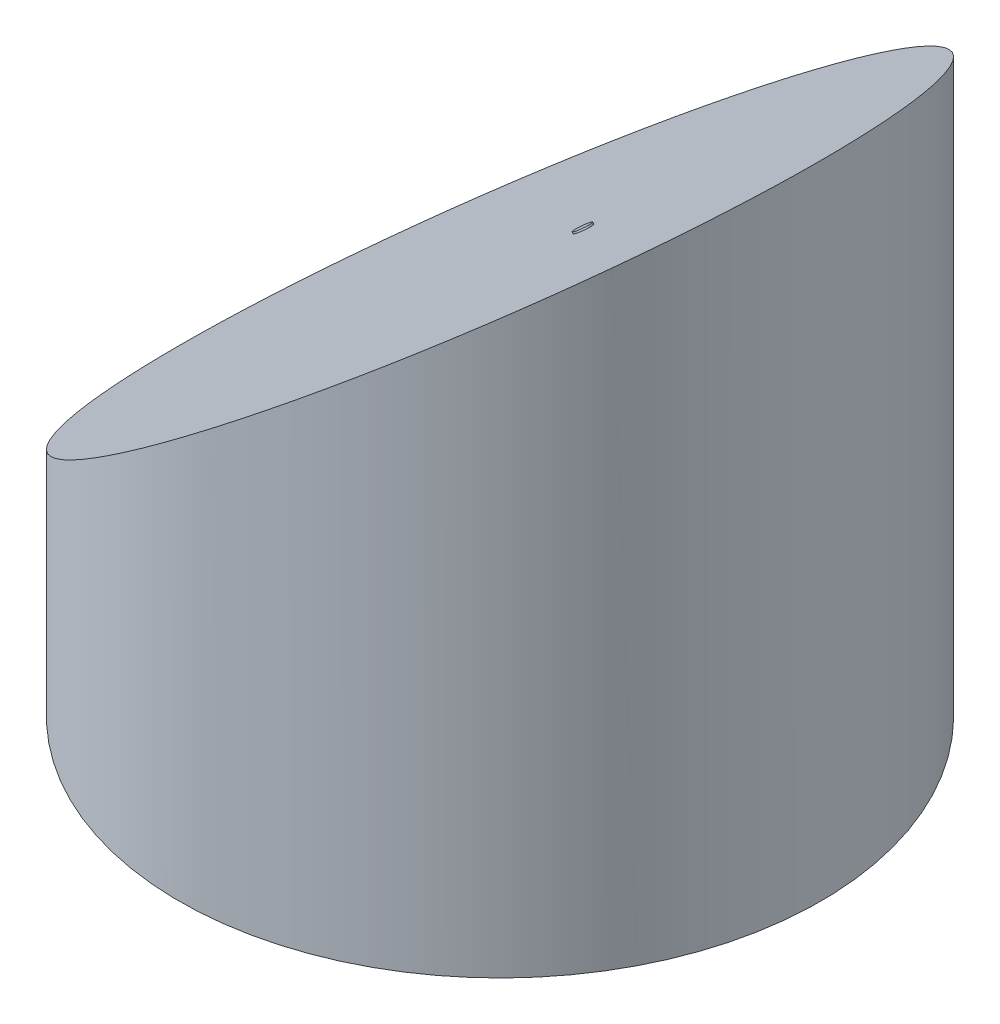
SolidWorks part; units mm, degrees
ref_plane "Front Plane" through (0, 0, 0) normal (0, 0, 1) x (1, 0, 0)
ref_plane "Top Plane" through (0, 0, 0) normal (0, 1, 0) x (1, 0, 0)
ref_plane "Right Plane" through (0, 0, 0) normal (1, 0, 0) x (0, 0, -1)
sketch "Sketch1" plane through (0, 0, 0) normal (0, 0, 1) x (1, 0, 0)
  line L0 (0, 3000) -> (0, -1000)
  line L1 (0, -1000) -> (-2000, -1000)
  line L2 (-2000, -1000) -> (-2000, 3000)
  line L3 (-2000, 3000) -> (0, 3000)
  dimension "D1" = 4000
  dimension "D2" = 2000
  dimension "D3" = 1000
revolve "Revolve1" add sketch "Sketch1" angle 360 about L0
sketch "Sketch2" plane through (0, 0, 0) normal (0, 0, 1) x (1, 0, 0)
  line L0 (2000, 3000) -> (-2000, 3000) construction
  line L1 (2000, 3000) -> (-2000, 3000)
  line L2 (-2000, 3000) -> (-2000, 1.0795)
  line L3 (-2000, 3000) -> (-2000, -1000) construction
  line L4 (-2000, 1.0795) -> (2000, 3000)
  dimension "D1" = 36.86
extrude "Cut-Extrude1" cut sketch "Sketch2" against normal through all both and the other way through all
sketch "Sketch3" plane through (-720.1865, 960.5943, 0) normal (-0.5999, 0.8001, 0) x (0.8001, 0.5999, 0)
  circle A1 centre (1550.4403, 0) radius 50
  ellipse E2 centre (900.1165, 0) end of major axis (3399.7927, 0) minor radius 2000
  ellipse E3 centre (900.1165, 0) end of major axis (3399.7927, 0) minor radius 2000 construction
  point P2 (0, 0)
  point P3 (0, 0)
  dimension "D3" = 100
  dimension "2968.75mm" = 3150
  dimension "D1" = 0
extrude "Boss-Extrude1" add sketch "Sketch3" along normal blind 10
